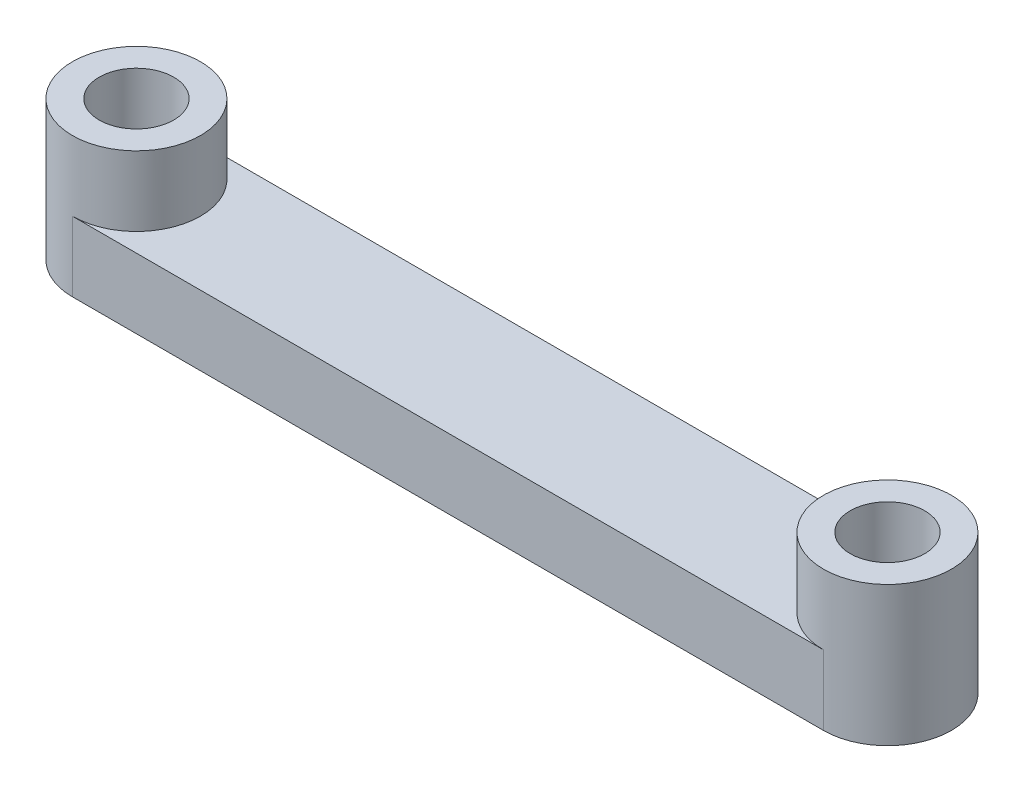
SolidWorks part; units mm, degrees
ref_plane "Alzado" through (0, 0, 0) normal (0, 0, 1) x (1, 0, 0)
ref_plane "Planta" through (0, 0, 0) normal (0, 1, 0) x (1, 0, 0)
ref_plane "Vista lateral" through (0, 0, 0) normal (1, 0, 0) x (0, 0, -1)
sketch "Croquis1" plane through (0, 0, 0) normal (0, 1, 0) x (1, 0, 0)
  line L0 (0, 0) -> (32.26, 0) construction
  line L1 (0, 2.75) -> (32.26, 2.75)
  line L2 (0, -2.75) -> (32.26, -2.75)
  circle A0 centre (0, 0) radius 1.6
  circle A1 centre (32.26, 0) radius 1.6
  circle A2 centre (0, 0) radius 2.75
  circle A3 centre (32.26, 0) radius 2.75
  dimension "D1" = 3.2
  dimension "D3" = 3.2
  dimension "D4" = 5.5
  dimension "D5" = 5.5
  dimension "D2" = 32.26
extrude "Saliente-Extruir1" add sketch "Croquis1" along normal blind 3
sketch "Croquis2" plane through (0, 3, 0) normal (0, 1, 0) x (1, 0, 0)
  circle A0 centre (0, 0) radius 2.75
  circle A1 centre (32.26, 0) radius 2.75
  circle A2 centre (32.26, 0) radius 1.6
  circle A3 centre (0, 0) radius 1.6
extrude "Saliente-Extruir2" add sketch "Croquis2" along normal blind 3
